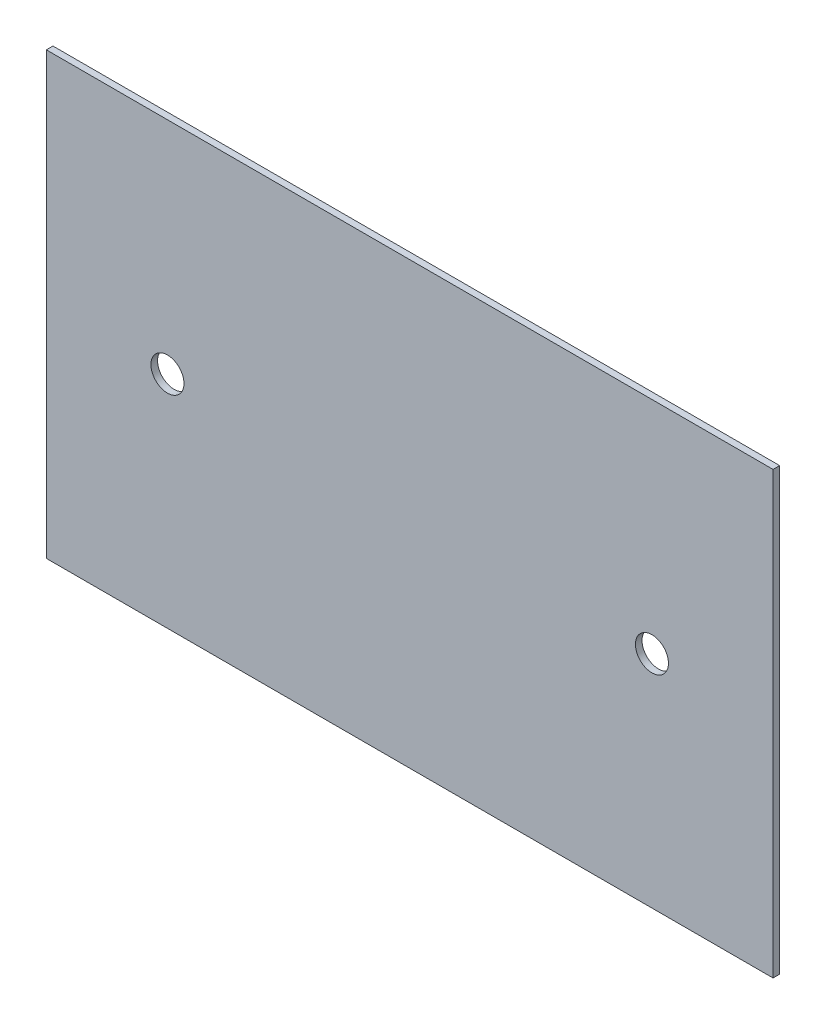
SolidWorks part; units mm, degrees
ref_plane "Alzado" through (0, 0, 0) normal (0, 0, 1) x (1, 0, 0)
ref_plane "Planta" through (0, 0, 0) normal (0, 1, 0) x (1, 0, 0)
ref_plane "Vista lateral" through (0, 0, 0) normal (1, 0, 0) x (0, 0, -1)
sketch "Croquis1" plane through (0, 0, 0) normal (0, 0, 1) x (1, 0, 0)
  line L1 (-165, 100) -> (165, 100)
  line L2 (-165, 100) -> (-165, -100)
  line L3 (-165, -100) -> (165, -100)
  line L4 (165, 100) -> (165, -100)
  line L5 (-165, 100) -> (165, -100) construction
  line L6 (-165, -100) -> (165, 100) construction
  point P0 (0, 0)
  dimension "D1" = 330
  dimension "D2" = 200
extrude "Saliente-Extruir1" add sketch "Croquis1" along normal blind 3
sketch "Croquis2" plane through (0, 0, 3) normal (0, 0, 1) x (1, 0, 0)
  line L0 (-165, 0) -> (165, 0) construction
  line L1 (-165, 100) -> (-165, -100) construction
  line L2 (165, -100) -> (165, 100) construction
  line L3 (0, 100) -> (0, -100) construction
  line L4 (165, 100) -> (-165, 100) construction
  line L5 (-165, -100) -> (165, -100) construction
  circle A0 centre (-110, 0) radius 7.5
  circle A1 centre (110, 0) radius 7.5
  dimension "D1" = 15
  dimension "D2" = 55
extrude "Cortar-Extruir1" cut sketch "Croquis2" against normal through all
equation "\"largo\"= 330mm"
equation "\"ancho\"= 200mm"
